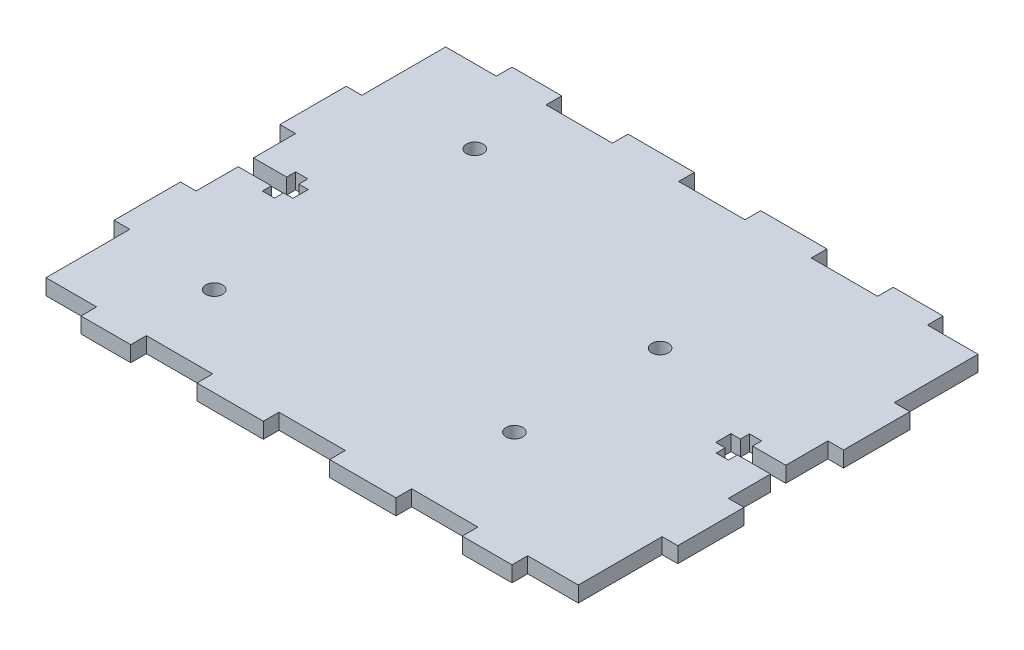
SolidWorks part; units mm, degrees
material "Acrylic (Medium-high impact)"
ref_plane "Front Plane" through (0, 0, 0) normal (0, 0, 1) x (1, 0, 0)
ref_plane "Top Plane" through (0, 0, 0) normal (0, 1, 0) x (1, 0, 0)
ref_plane "Right Plane" through (0, 0, 0) normal (1, 0, 0) x (0, 0, -1)
sketch "Sketch1" plane through (0, 0, 0) normal (0, 1, 0) x (1, 0, 0)
  line L1 (0, 0) -> (107.95, 0)
  line L2 (0, 0) -> (0, 82.55)
  line L3 (0, 82.55) -> (107.95, 82.55)
  line L4 (107.95, 0) -> (107.95, 82.55)
  dimension "D20" = 82.55
  dimension "D21" = 107.95
extrude "Boss-Extrude1" add sketch "Sketch1" along normal blind 3
sketch "Sketch3" plane through (0, 3, 0) normal (0, 1, 0) x (1, 0, 0)
  line L0 (22.225, 0) -> (34.925, 0)
  line L1 (0, 0) -> (107.95, 0) construction
  line L2 (34.925, 0) -> (34.925, 3)
  line L3 (34.925, 3) -> (22.225, 3)
  line L4 (22.225, 3) -> (22.225, 0)
  line L5 (53.975, 0) -> (53.975, 82.55) construction
  line L6 (107.95, 82.55) -> (0, 82.55) construction
  line L7 (107.95, 41.275) -> (0, 41.275) construction
  line L8 (107.95, 0) -> (107.95, 82.55) construction
  line L9 (0, 82.55) -> (0, 0) construction
  line L10 (73.025, 3) -> (85.725, 3)
  line L11 (85.725, 3) -> (85.725, 0)
  line L12 (85.725, 0) -> (73.025, 0)
  line L13 (73.025, 0) -> (73.025, 3)
  line L14 (85.725, 79.55) -> (85.725, 82.55)
  line L15 (85.725, 82.55) -> (73.025, 82.55)
  line L16 (73.025, 79.55) -> (85.725, 79.55)
  line L17 (0, 50.8) -> (3, 50.8)
  line L18 (22.225, 79.55) -> (22.225, 82.55)
  line L19 (22.225, 82.55) -> (34.925, 82.55)
  line L20 (34.925, 79.55) -> (22.225, 79.55)
  line L21 (34.925, 82.55) -> (34.925, 79.55)
  line L22 (53.975, 3) -> (60.325, 3)
  line L23 (60.325, 3) -> (60.325, 0)
  line L24 (60.325, 0) -> (53.975, 0)
  line L25 (53.975, 0) -> (47.625, 0)
  line L26 (47.625, 0) -> (47.625, 3)
  line L27 (47.625, 3) -> (53.975, 3)
  line L28 (60.325, 82.55) -> (53.975, 82.55)
  line L29 (53.975, 82.55) -> (47.625, 82.55)
  line L30 (47.625, 82.55) -> (47.625, 79.55)
  line L31 (47.625, 79.55) -> (53.975, 79.55)
  line L32 (53.975, 79.55) -> (60.325, 79.55)
  line L33 (60.325, 79.55) -> (60.325, 82.55)
  line L34 (73.025, 82.55) -> (73.025, 79.55)
  line L35 (3, 50.8) -> (3, 31.75)
  line L36 (3, 31.75) -> (0, 31.75)
  line L37 (0, 31.75) -> (0, 50.8)
  line L38 (0, 19.05) -> (3, 19.05)
  line L39 (3, 19.05) -> (3, 3)
  line L40 (3, 3) -> (12.7, 3)
  line L41 (0, 3) -> (0, 19.05)
  line L42 (107.95, 0) -> (107.95, 3)
  line L43 (0, 79.55) -> (0, 63.5)
  line L44 (0, 63.5) -> (3, 63.5)
  line L45 (3, 63.5) -> (3, 79.55)
  line L46 (95.25, 0) -> (107.95, 0)
  line L47 (107.95, 3) -> (107.95, 19.05)
  line L48 (107.95, 19.05) -> (104.95, 19.05)
  line L49 (104.95, 19.05) -> (104.95, 3)
  line L50 (104.95, 31.75) -> (107.95, 31.75)
  line L51 (107.95, 31.75) -> (107.95, 50.8)
  line L52 (104.95, 50.8) -> (104.95, 31.75)
  line L53 (107.95, 50.8) -> (104.95, 50.8)
  line L54 (107.95, 63.5) -> (104.95, 63.5)
  line L55 (95.25, 3) -> (95.25, 0)
  line L56 (107.95, 79.55) -> (107.95, 63.5)
  line L57 (104.95, 63.5) -> (104.95, 79.55)
  line L58 (12.7, 3) -> (12.7, 0)
  line L59 (12.7, 0) -> (0, 0)
  line L60 (0, 0) -> (0, 3)
  line L61 (104.95, 3) -> (95.25, 3)
  line L62 (0, 82.55) -> (0, 79.55)
  line L63 (12.7, 82.55) -> (0, 82.55)
  line L64 (12.7, 79.55) -> (12.7, 82.55)
  line L65 (3, 79.55) -> (12.7, 79.55)
  line L66 (107.95, 82.55) -> (107.95, 79.55)
  line L67 (95.25, 82.55) -> (107.95, 82.55)
  line L68 (95.25, 79.55) -> (95.25, 82.55)
  line L69 (104.95, 79.55) -> (95.25, 79.55)
  dimension "D1" = 3
  dimension "D2" = 12.7
  dimension "D3" = 12.7
  dimension "D4" = 12.7
  dimension "D5" = 3
  dimension "D6" = 19.05
  dimension "D7" = 12.7
  dimension "D8" = 12.7
extrude "Cut-Extrude2" cut sketch "Sketch3" against normal up to next
sketch "Sketch4" plane through (0, 3, 0) normal (0, 1, 0) x (1, 0, 0)
  circle A0 centre (22.6875, 65.425) radius 1.6 construction
  circle A1 centre (21.0875, 17.125) radius 1.6 construction
  circle A2 centre (73.4875, 22.225) radius 1.6 construction
  circle A3 centre (73.4875, 50.125) radius 1.6 construction
  circle A4 centre (22.6875, 65.425) radius 1.6
  circle A5 centre (21.0875, 17.125) radius 1.6
  circle A6 centre (73.4875, 22.225) radius 1.6
  circle A7 centre (73.4875, 50.125) radius 1.6
extrude "Cut-Extrude3" cut sketch "Sketch4" against normal up to next
sketch "Sketch5" [suppressed] plane through (0, 3, 0) normal (0, 1, 0) x (1, 0, 0)
  circle A0 centre (53.8825, 22.7594) radius 5.9436 construction
  circle A1 centre (53.7182, 58.8647) radius 5.9531 construction
  circle A2 centre (53.8825, 22.7594) radius 5.9436 construction
  circle A3 centre (53.7182, 58.8647) radius 5.9531 construction
  circle A4 centre (53.7182, 58.8647) radius 5.9563
  circle A5 centre (53.8825, 22.7594) radius 5.9563
  dimension "D1" = 11.9062
  dimension "D2" = 11.8872
  dimension "D3" = 11.9126
  dimension "D4" = 11.9126
extrude "Cut-Extrude4" [suppressed] cut sketch "Sketch5" against normal up to next
sketch "Sketch6" plane through (0, 3, 0) normal (0, 1, 0) x (1, 0, 0)
  line L0 (3, 39.8145) -> (9.35, 39.8145)
  line L1 (9.35, 38.0873) -> (11.6868, 38.0873)
  line L2 (11.6868, 38.0873) -> (11.6868, 39.8145)
  line L3 (11.6868, 39.8145) -> (13.4938, 39.8145)
  line L4 (13.4938, 39.8145) -> (13.4938, 41.275)
  line L5 (9.35, 39.8145) -> (9.35, 38.0873)
  line L6 (3, 39.8145) -> (3, 41.275)
  line L7 (3, 50.8) -> (3, 31.75) construction
  line L8 (107.95, 41.275) -> (0, 41.275) construction
  line L9 (107.95, 41.275) -> (0, 41.275) construction
  line L10 (3, 42.7355) -> (3, 41.275)
  line L11 (3, 42.7355) -> (9.35, 42.7355)
  line L12 (9.35, 42.7355) -> (9.35, 44.4627)
  line L13 (9.35, 44.4627) -> (11.6868, 44.4627)
  line L14 (11.6868, 44.4627) -> (11.6868, 42.7355)
  line L15 (11.6868, 42.7355) -> (13.4938, 42.7355)
  line L16 (13.4938, 42.7355) -> (13.4938, 41.275)
  line L17 (53.975, 0) -> (53.975, 82.55) construction
  line L18 (53.975, 0) -> (53.975, 82.55) construction
  line L19 (94.4562, 42.7355) -> (94.4562, 41.275)
  line L20 (96.2632, 42.7355) -> (94.4562, 42.7355)
  line L21 (96.2632, 44.4627) -> (96.2632, 42.7355)
  line L22 (98.6, 44.4627) -> (96.2632, 44.4627)
  line L23 (98.6, 42.7355) -> (98.6, 44.4627)
  line L24 (104.95, 42.7355) -> (98.6, 42.7355)
  line L25 (104.95, 42.7355) -> (104.95, 41.275)
  line L26 (104.95, 39.8145) -> (104.95, 41.275)
  line L27 (104.95, 39.8145) -> (98.6, 39.8145)
  line L28 (98.6, 39.8145) -> (98.6, 38.0873)
  line L29 (98.6, 38.0873) -> (96.2632, 38.0873)
  line L30 (96.2632, 38.0873) -> (96.2632, 39.8145)
  line L31 (96.2632, 39.8145) -> (94.4562, 39.8145)
  line L32 (94.4562, 39.8145) -> (94.4562, 41.275)
  dimension "D1" = 10.4938
  dimension "D2" = 2.3368
  dimension "D3" = 6.3754
  dimension "D4" = 2.921
  dimension "D5" = 2.921
  dimension "D6" = 6.35
extrude "Cut-Extrude5" cut sketch "Sketch6" against normal up to next
equation "\"D1@Sketch3\" = \"D1@Boss-Extrude1\""
equation "\"tab_size\"= 0.5"
equation "\"D2@Sketch3\" = \"tab_size\""
equation "\"D3@Sketch3\"  =  \"tab_size\""
equation "\"D5@Sketch3\" = \"D1@Sketch3\""
equation "\"D7@Sketch3\" = \"tab_size\""
